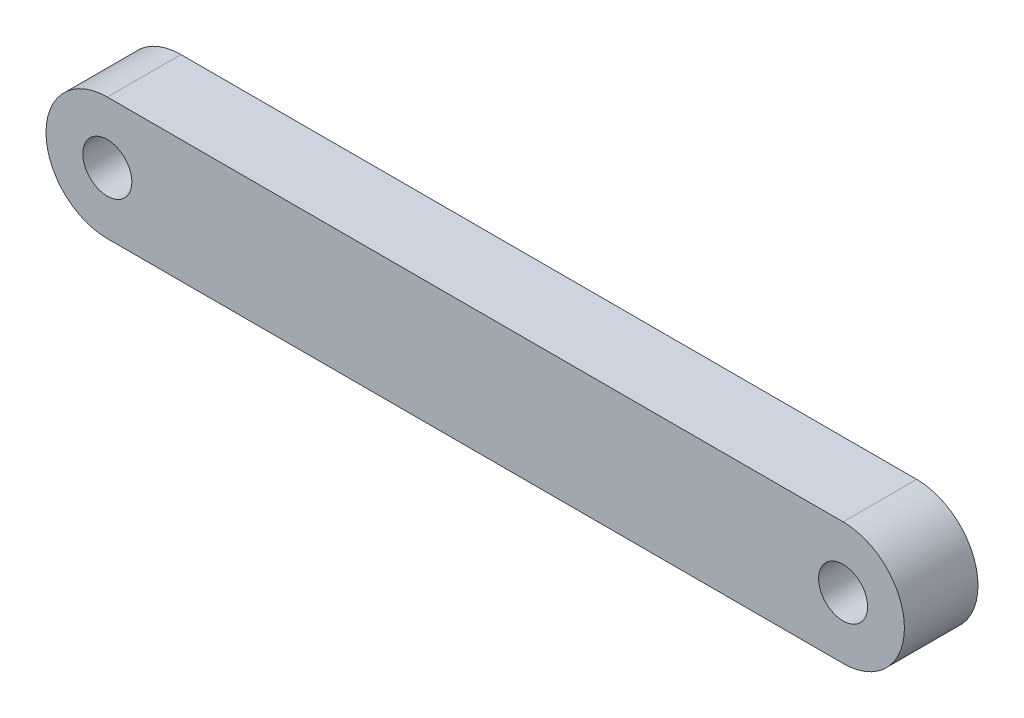
SolidWorks part; units mm, degrees
ref_plane "前视基准面" through (0, 0, 0) normal (0, 0, 1) x (1, 0, 0)
ref_plane "上视基准面" through (0, 0, 0) normal (0, 1, 0) x (1, 0, 0)
ref_plane "右视基准面" through (0, 0, 0) normal (1, 0, 0) x (0, 0, -1)
sketch "草图1" plane through (0, 0, 0) normal (0, 0, 1) x (1, 0, 0)
  line L0 (0, 0) -> (30, 0) construction
  line L2 (0, 2.5) -> (30, 2.5)
  line L3 (0, -2.5) -> (30, -2.5)
  arc A0 (0, 2.5) -> (0, -2.5) centre (0, 0) ccw
  arc A1 (30, -2.5) -> (30, 2.5) centre (30, 0) ccw
  circle A2 centre (0, 0) radius 1
  circle A3 centre (30, 0) radius 1
  point P5 (15, 0)
  dimension "D3" = 2
  dimension "D4" = 2
  dimension "D1" = 30
  dimension "D2" = 5
extrude "凸台-拉伸1" add sketch "草图1" along normal blind 3
